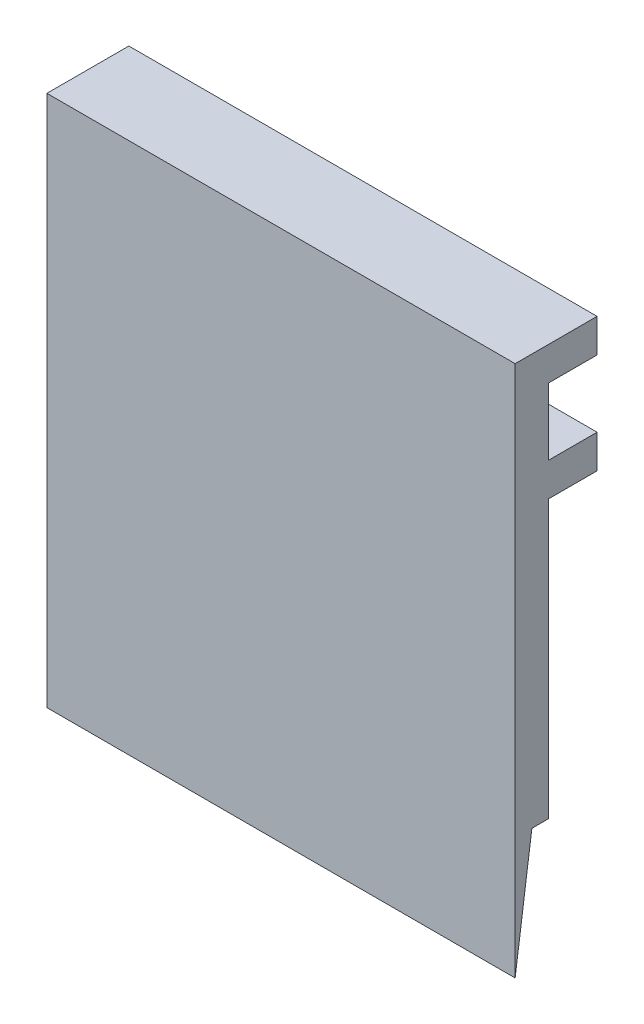
SolidWorks part; units mm, degrees
ref_plane "Front Plane" through (0, 0, 0) normal (0, 0, 1) x (1, 0, 0)
ref_plane "Top Plane" through (0, 0, 0) normal (0, 1, 0) x (1, 0, 0)
ref_plane "Right Plane" through (0, 0, 0) normal (1, 0, 0) x (0, 0, -1)
sketch "Sketch1" plane through (0, 0, 0) normal (0, 1, 0) x (1, 0, 0)
  line L1 (0, 0) -> (27.998, 0)
  line L2 (0, 0) -> (0, 2)
  line L3 (0, 2) -> (27.998, 2)
  line L4 (27.998, 0) -> (27.998, 2)
  dimension "D1" = 27.998
  dimension "D2" = 2
extrude "Boss-Extrude1" add sketch "Sketch1" along normal blind 10
sketch "Sketch3" plane through (27.998, 0, 0) normal (1, 0, 0) x (0, 0, -1)
  line L0 (1, 8.25) -> (2, 8.25) construction
  line L1 (0, 1) -> (1, 8.25) construction
  line L2 (1, 8.25) -> (2, 8.25)
  line L3 (0, 1) -> (1, 8.25)
  line L4 (0, 1) -> (0, 0)
  line L5 (0, 0) -> (2, 0)
  line L6 (2, 0) -> (2, 8.25)
extrude "Cut-Extrude1" cut sketch "Sketch3" against normal blind 32
sketch "Sketch4" plane through (0, 10, 0) normal (0, 1, 0) x (1, 0, 0)
  line L1 (0, 0) -> (27.998, 0)
  line L2 (0, 0) -> (0, 2)
  line L3 (0, 2) -> (27.998, 2)
  line L4 (27.998, 0) -> (27.998, 2)
extrude "Boss-Extrude2" add sketch "Sketch4" along normal blind 22.8123
sketch "Sketch5" plane through (27.998, 0, 0) normal (1, 0, 0) x (0, 0, -1)
  line L0 (2, 32.8123) -> (2, 8.25) construction
  line L1 (0, 32.8123) -> (4.9, 32.8123)
  line L2 (0, 32.8123) -> (0, 30.8123)
  line L3 (0, 30.8123) -> (4.9, 30.8123)
  line L4 (4.9, 32.8123) -> (4.9, 30.8123)
  line L5 (0, 32.8123) -> (0, 1) construction
  line L6 (0, 24.8123) -> (4.9, 24.8123)
  line L7 (0, 24.8123) -> (0, 26.8123)
  line L8 (0, 26.8123) -> (4.9, 26.8123)
  line L9 (4.9, 24.8123) -> (4.9, 26.8123)
  dimension "D1" = 2
  dimension "D2" = 2.9
  dimension "D3" = 4
  dimension "D4" = 2
extrude "Boss-Extrude3" add sketch "Sketch5" against normal up to surface (27.998 mm away) up to face at (0, 16.6249, -1)
